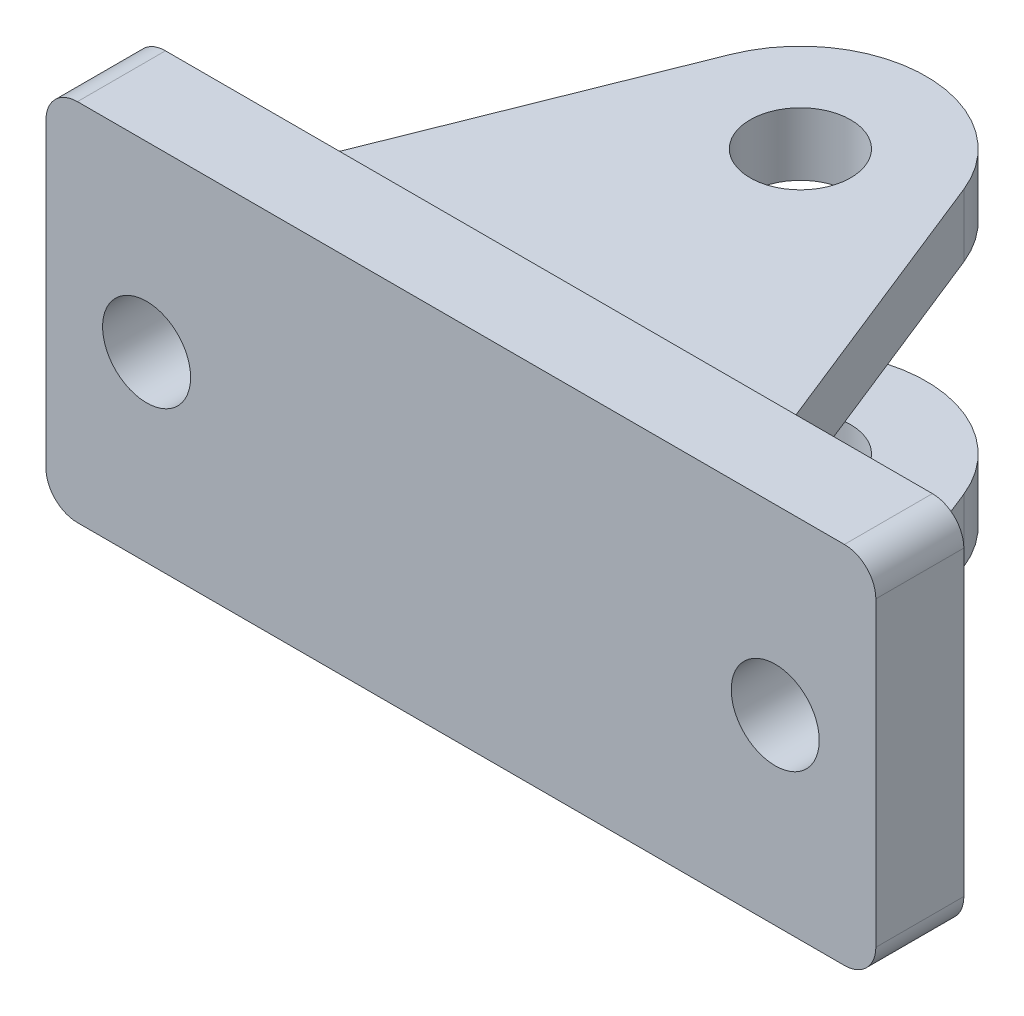
SolidWorks part; units mm, degrees
ref_plane "Front Plane" through (0, 0, 0) normal (0, 0, 1) x (1, 0, 0)
ref_plane "Top Plane" through (0, 0, 0) normal (0, 1, 0) x (1, 0, 0)
ref_plane "Right Plane" through (0, 0, 0) normal (1, 0, 0) x (0, 0, -1)
sketch "Sketch1" plane through (0, 0, 0) normal (0, 0, 1) x (1, 0, 0)
  line L0 (-14.1208, 0) -> (18.9445, 0) construction
  line L1 (-66, 29) -> (66, 29)
  line L2 (-66, 29) -> (-66, -29)
  line L3 (-66, -29) -> (66, -29)
  line L4 (66, 29) -> (66, -29)
  line L5 (-66, 29) -> (66, -29) construction
  line L6 (-66, -29) -> (66, 29) construction
  circle A0 centre (-50, 0) radius 7
  circle A1 centre (50, 0) radius 7
  point P0 (0, 0)
  dimension "D3" = 14
  dimension "D4" = 14
  dimension "D1" = 132
  dimension "D2" = 58
  dimension "D5" = 100
  dimension "D6" = 50
  dimension "D7" = 29
  dimension "D8" = 29
extrude "Boss-Extrude1" add sketch "Sketch1" along normal blind 14
fillet "Fillet1" radius 5 4 edges at (-66, 29, 7) (66, 29, 7) (66, -29, 7) (-66, -29, 7)
ref_plane "Plane1" through (0, -26, 0) normal (0, -1, 0) x (-1, 0, 0)
sketch "Sketch2" plane through (0, -26, 0) normal (0, -1, 0) x (-1, 0, 0)
  line L0 (0, -23.6824) -> (0, 45.2989) construction
  line L1 (-37.5, 0) -> (-18.575, 47.4141)
  line L2 (61, 0) -> (-61, 0) construction
  line L3 (18.575, 47.4141) -> (37.5, 0)
  line L4 (61, -14) -> (-61, -14) construction
  line L5 (-37.5, 0) -> (37.5, 0)
  arc A0 (18.575, 47.4141) -> (-18.575, 47.4141) centre (0, 40) ccw
  circle A1 centre (0, 40) radius 8
  dimension "D1" = 40
  dimension "D4" = 16
  dimension "D2" = 75
  dimension "D3" = 37.5
  dimension "D5" = 54
extrude "Boss-Extrude2" add sketch "Sketch2" against normal blind 10
fillet "Fillet2" radius 5 2 edges at (37.5, -21, 0) (-37.5, -21, 0)
mirror "Mirror1" about plane through (0, 0, 0) normal (0, 1, 0) of "Fillet2", "Boss-Extrude2"
